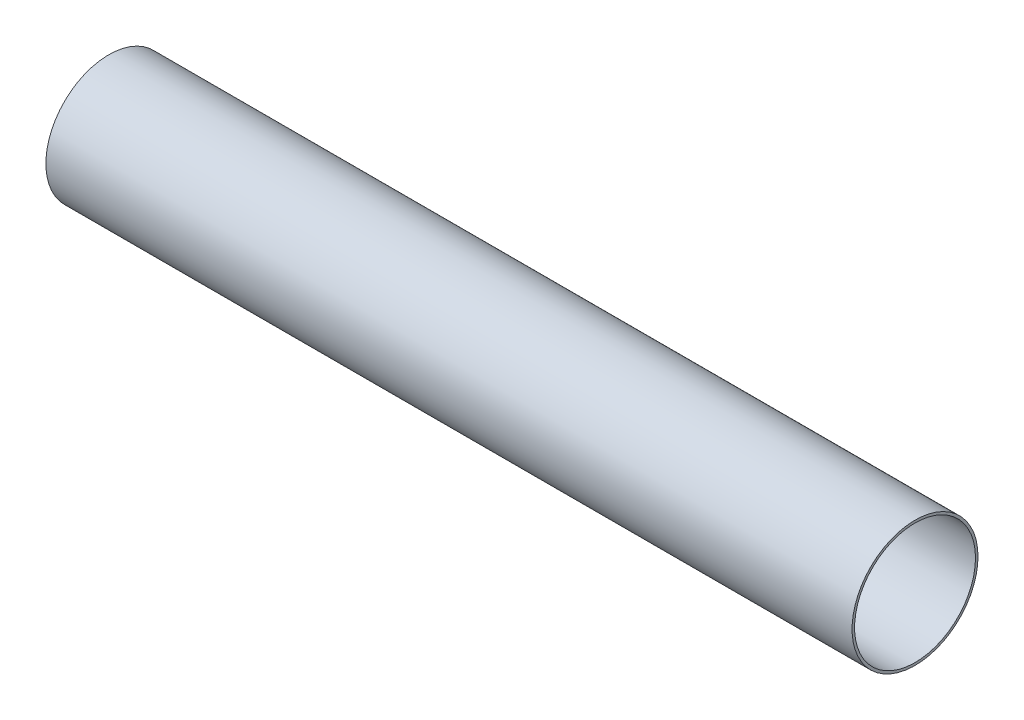
SolidWorks part; units mm, degrees
ref_plane "Front Plane" through (0, 0, 0) normal (0, 0, 1) x (1, 0, 0)
ref_plane "Top Plane" through (0, 0, 0) normal (0, 1, 0) x (1, 0, 0)
ref_plane "Right Plane" through (0, 0, 0) normal (1, 0, 0) x (0, 0, -1)
sketch "Sketch1" plane through (0, 0, 0) normal (1, 0, 0) x (0, 0, -1)
  circle A0 centre (0, 0) radius 39.6748
  circle A2 centre (0, 0) radius 38.1
  dimension "D1" = 79.3496
  dimension "D2" = 76.2
extrude "Boss-Extrude1" add sketch "Sketch1" along normal blind 508
